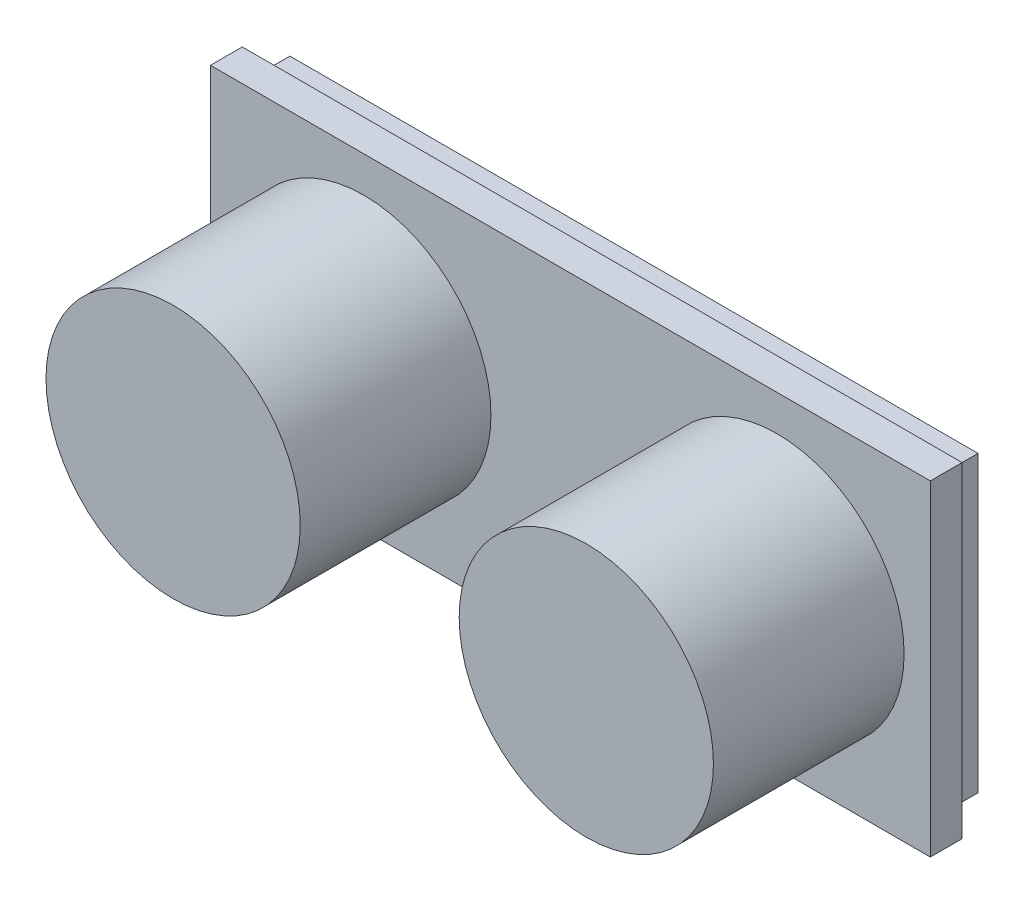
SolidWorks part; units mm, degrees
ref_plane "Front Plane" through (0, 0, 0) normal (0, 0, 1) x (1, 0, 0)
ref_plane "Top Plane" through (0, 0, 0) normal (0, 1, 0) x (1, 0, 0)
ref_plane "Right Plane" through (0, 0, 0) normal (1, 0, 0) x (0, 0, -1)
sketch "Sketch1" plane through (0, 0, 0) normal (0, 0, 1) x (1, 0, 0)
  line L1 (-22.65, -10.25) -> (22.65, -10.25)
  line L2 (-22.65, -10.25) -> (-22.65, 10.25)
  line L3 (-22.65, 10.25) -> (22.65, 10.25)
  line L4 (22.65, -10.25) -> (22.65, 10.25)
  line L5 (-22.65, -10.25) -> (22.65, 10.25) construction
  line L6 (-22.65, 10.25) -> (22.65, -10.25) construction
  point P0 (0, 0)
  dimension "D1" = 45.3
  dimension "D2" = 20.5
extrude "Boss-Extrude1" add sketch "Sketch1" along normal blind 2
sketch "Sketch2" plane through (0, 0, 0) normal (0, 0, -1) x (-1, 0, 0)
  line L1 (-5, -17.25) -> (5, -17.25)
  line L2 (-5, -17.25) -> (-5, -7.25)
  line L3 (-5, -7.25) -> (5, -7.25)
  line L4 (5, -17.25) -> (5, -7.25)
  line L5 (22.65, -10.25) -> (-22.65, -10.25) construction
  point P6 (0, -7.25)
  dimension "D1" = 10
  dimension "D2" = 10
  dimension "D3" = 3
extrude "Boss-Extrude2" add sketch "Sketch2" along normal blind 4
sketch "Sketch3" plane through (0, 0, 2) normal (0, 0, 1) x (1, 0, 0)
  line L0 (0, 0) -> (0, 19.9252) construction
  circle A0 centre (13, 0) radius 8
  circle A1 centre (-13, 0) radius 8
  point P7 (0, 0)
  dimension "D1" = 16
  dimension "D2" = 13
extrude "Boss-Extrude3" add sketch "Sketch3" along normal blind 12
sketch "Sketch4" plane through (0, 0, 0) normal (0, 0, -1) x (-1, 0, 0)
  line L16 (-6, -9.25) -> (-6, -6.25)
  line L17 (-6, -6.25) -> (6, -6.25)
  line L18 (6, -6.25) -> (6, -9.25)
  line L19 (6, -9.25) -> (21.65, -9.25)
  line L20 (21.65, -9.25) -> (21.65, 9.25)
  line L21 (21.65, 9.25) -> (-21.65, 9.25)
  line L22 (-21.65, 9.25) -> (-21.65, -9.25)
  line L23 (-21.65, -9.25) -> (-6, -9.25)
  line L24 (-6, -9.25) -> (-6, -6.25)
  line L25 (-6, -6.25) -> (6, -6.25)
  line L26 (6, -6.25) -> (6, -9.25)
  line L27 (6, -9.25) -> (21.65, -9.25)
  line L28 (21.65, -9.25) -> (21.65, 9.25)
  line L29 (21.65, 9.25) -> (-21.65, 9.25)
  line L30 (-21.65, 9.25) -> (-21.65, -9.25)
  line L31 (-21.65, -9.25) -> (-6, -9.25)
  dimension "D1" = 1
extrude "Boss-Extrude4" add sketch "Sketch4" along normal blind 2
